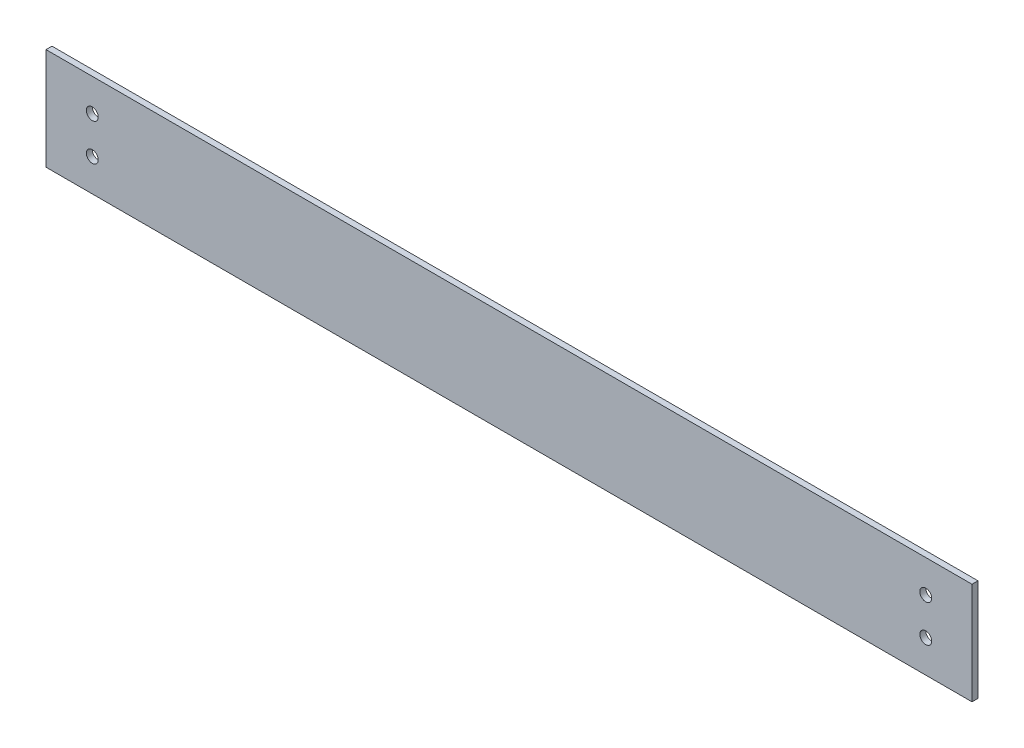
SolidWorks part; units mm, degrees
ref_plane "Front Plane" through (0, 0, 0) normal (0, 0, 1) x (1, 0, 0)
ref_plane "Top Plane" through (0, 0, 0) normal (0, 1, 0) x (1, 0, 0)
ref_plane "Right Plane" through (0, 0, 0) normal (1, 0, 0) x (0, 0, -1)
sketch "Sketch1" plane through (0, 0, 0) normal (0, 0, 1) x (1, 0, 0)
  line L1 (0, 0) -> (254, 0)
  line L2 (0, 0) -> (0, 27.94)
  line L3 (0, 27.94) -> (254, 27.94)
  line L4 (254, 0) -> (254, 27.94)
  dimension "D1" = 254
  dimension "D2" = 27.94
extrude "Boss-Extrude1" add sketch "Sketch1" along normal blind 1.6383
sketch "Sketch2" plane through (0, 0, 1.6383) normal (0, 0, 1) x (1, 0, 0)
  line L0 (127, 27.94) -> (127, 0) construction
  line L1 (254, 27.94) -> (0, 27.94) construction
  line L2 (0, 0) -> (254, 0) construction
  line L3 (127, 0) -> (127, 13.97) construction
  line L4 (127, 13.97) -> (0, 13.97) construction
  line L5 (0, 27.94) -> (0, 0) construction
  circle A0 centre (12.7, 8.89) radius 1.632
  circle A1 centre (12.7, 19.05) radius 1.6319
  circle A2 centre (241.3, 8.89) radius 1.632
  circle A3 centre (241.3, 19.05) radius 1.632
  dimension "D3" = 3.2639
  dimension "D1" = 5.08
  dimension "D2" = 114.3
extrude "Cut-Extrude1" cut sketch "Sketch2" against normal through all
